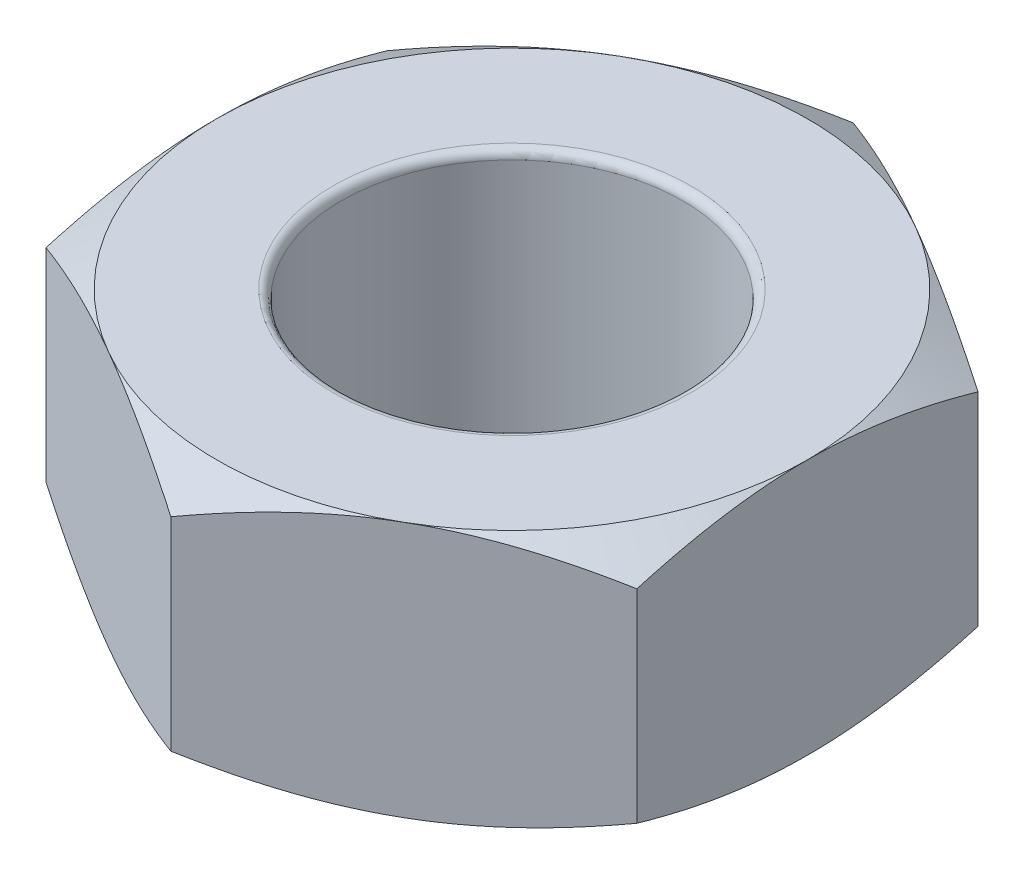
SolidWorks part; units mm, degrees
ref_plane "Front Plane" through (0, 0, 0) normal (0, 0, 1) x (1, 0, 0)
ref_plane "Top Plane" through (0, 0, 0) normal (0, 1, 0) x (1, 0, 0)
ref_plane "Right Plane" through (0, 0, 0) normal (1, 0, 0) x (0, 0, -1)
sketch "Sketch1" plane through (0, 0, 0) normal (0, 1, 0) x (1, 0, 0)
  line L1 (0, 2) -> (-1.7321, 1)
  line L2 (-1.7321, 1) -> (-1.7321, -1)
  line L3 (-1.7321, -1) -> (0, -2)
  line L4 (0, -2) -> (1.7321, -1)
  line L5 (1.7321, -1) -> (1.7321, 1)
  line L6 (1.7321, 1) -> (0, 2)
  circle A0 centre (0, 0) radius 1
  circle A1 centre (0, 0) radius 1.7321 construction
  dimension "D1" = 2
  dimension "D2" = 4
extrude "Boss-Extrude1" add sketch "Sketch1" along normal blind 1.5
sketch "Sketch2" plane through (0, 1.5, 0) normal (0, 1, 0) x (1, 0, 0)
  circle A0 centre (0, 0) radius 1.7321 construction
  circle A1 centre (0, 0) radius 1.7321
extrude "Cut-Extrude1" cut sketch "Sketch2" against normal blind 2 draft 60 flip side to cut
sketch "Sketch3" plane through (0, 0, 0) normal (0, -1, 0) x (1, 0, 0)
  circle A0 centre (0, 0) radius 1.7321 construction
  circle A1 centre (0, 0) radius 1.7321
extrude "Cut-Extrude2" cut sketch "Sketch3" against normal blind 2 draft 60 flip side to cut
fillet "Fillet1" radius 0.05 2 edges at (0, 0, 1) (0, 1.5, 1)
